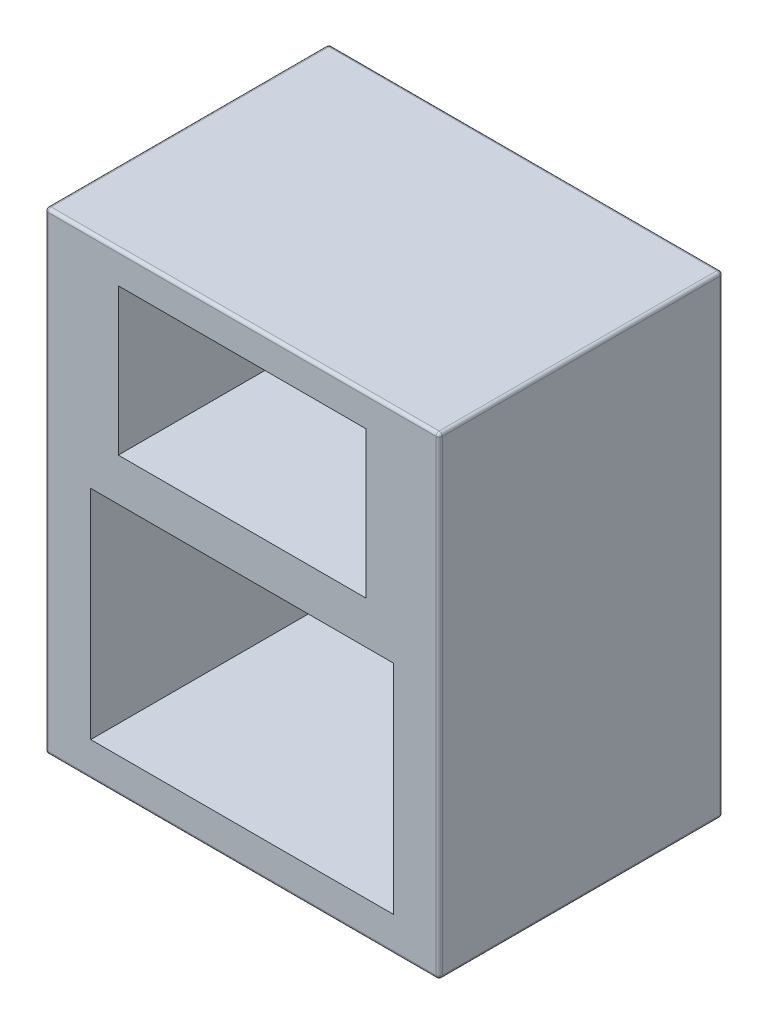
SolidWorks part; units mm, degrees
ref_plane "前视基准面" through (0, 0, 0) normal (0, 0, 1) x (1, 0, 0)
ref_plane "上视基准面" through (0, 0, 0) normal (0, 1, 0) x (1, 0, 0)
ref_plane "右视基准面" through (0, 0, 0) normal (1, 0, 0) x (0, 0, -1)
sketch "草图1" plane through (0, 0, 0) normal (0, 0, 1) x (1, 0, 0)
  line L1 (0, 0) -> (250, 0)
  line L2 (0, 0) -> (0, 300)
  line L3 (0, 300) -> (250, 300)
  line L4 (250, 0) -> (250, 300)
  dimension "D1" = 250
  dimension "D2" = 300
extrude "凸台-拉伸1" add sketch "草图1" along normal blind 180
fillet "圆角1" radius 2 12 edges at (0, 0, 90) (125, 0, 0) (0, 150, 0) (250, 0, 90) (250, 150, 0) (250, 300, 90) (0, 300, 90) (125, 300, 0) (125, 300, 180) (250, 150, 180) (125, 0, 180) (0, 150, 180)
sketch "草图2" plane through (0, 0, 180) normal (0, 0, 1) x (1, 0, 0)
  line L0 (0, 150) -> (255.14, 150) construction
  line L2 (0, 2) -> (0, 298) construction
  line L3 (203.5, 280) -> (203.5, 187)
  line L12 (221, 160) -> (221, 22)
  line L13 (29, 22) -> (221, 22)
  line L14 (29, 160) -> (29, 22)
  line L15 (29, 160) -> (221, 160)
  line L16 (46.5, 187) -> (203.5, 187)
  line L17 (46.5, 280) -> (46.5, 187)
  line L18 (46.5, 280) -> (203.5, 280)
extrude "切除-拉伸1" cut sketch "草图2" against normal up to next
